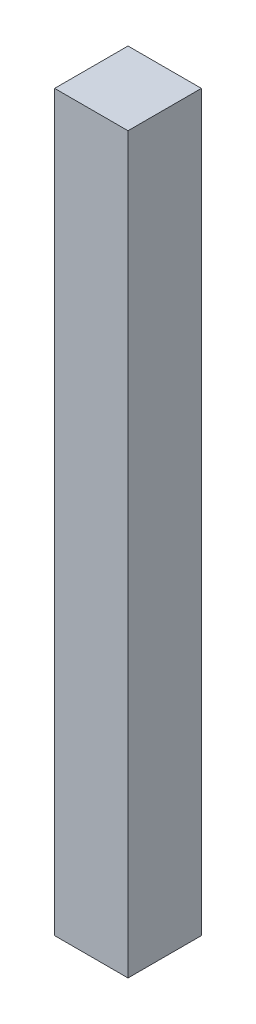
SolidWorks part; units mm, degrees
ref_plane "Plan de face" through (0, 0, 0) normal (0, 0, 1) x (1, 0, 0)
ref_plane "Plan de dessus" through (0, 0, 0) normal (0, 1, 0) x (1, 0, 0)
ref_plane "Plan de droite" through (0, 0, 0) normal (1, 0, 0) x (0, 0, -1)
sketch "Esquisse1" plane through (0, 0, 0) normal (0, 0, 1) x (1, 0, 0)
  line L1 (-29.9144, 26.8449) -> (-24.9144, 26.8449)
  line L2 (-29.9144, 26.8449) -> (-29.9144, -23.1551)
  line L3 (-29.9144, -23.1551) -> (-24.9144, -23.1551)
  line L4 (-24.9144, 26.8449) -> (-24.9144, -23.1551)
  dimension "D1" = 50
  dimension "D2" = 5
extrude "Boss.-Extru.1" add sketch "Esquisse1" along normal blind 5
